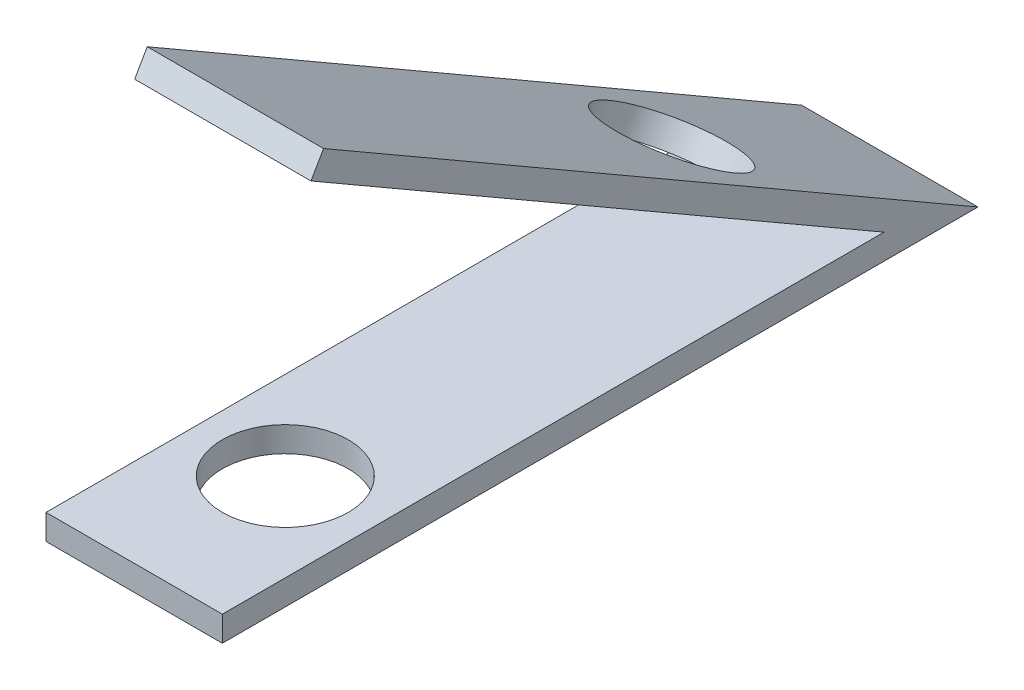
SolidWorks part; units mm, degrees
ref_plane "Front Plane" through (0, 0, 0) normal (0, 0, 1) x (1, 0, 0)
ref_plane "Top Plane" through (0, 0, 0) normal (0, 1, 0) x (1, 0, 0)
ref_plane "Right Plane" through (0, 0, 0) normal (1, 0, 0) x (0, 0, -1)
sketch "Sketch1" plane through (0, 0, 0) normal (1, 0, 0) x (0, 0, -1)
  line L0 (-227.4871, 131.3397) -> (0, 0)
  line L1 (0, 0) -> (-262.6795, 0)
  line L2 (-262.6795, 0) -> (-262.6795, -10)
  line L3 (-262.6795, -10) -> (37.3205, -10)
  line L4 (37.3205, -10) -> (-222.4871, 140)
  line L5 (-222.4871, 140) -> (-227.4871, 131.3397)
  dimension "D1" = 10
  dimension "D2" = 10
  dimension "D3" = 300
  dimension "D4" = 300
  dimension "D5" = 30
extrude "Boss-Extrude1" add sketch "Sketch1" along normal blind 70
sketch "Sketch2" plane through (0, 8.6603, -5) normal (0, 0.866, -0.5) x (1, 0, 0)
  line L0 (0, 37.3205) -> (0, -262.6795) construction
  line L3 (70, 37.3205) -> (0, 37.3205) construction
  circle A0 centre (35, -62.6795) radius 25
  dimension "D1" = 50
  dimension "D2" = 35
  dimension "D3" = 100
extrude "Cut-Extrude1" cut sketch "Sketch2" against normal blind 10
sketch "Sketch5" plane through (0, 0, 0) normal (0, 1, 0) x (1, 0, 0)
  line L0 (70, -262.6795) -> (0, -262.6795) construction
  line L1 (70, 37.3205) -> (70, -222.4871) construction
  circle A0 centre (35, -202.6795) radius 25
  dimension "D1" = 50
  dimension "D2" = 60
  dimension "D3" = 35
extrude "Cut-Extrude3" cut sketch "Sketch5" against normal blind 300
equation "\"mountAngle\" = 30deg"
equation "\"D5@Sketch1\"=\"mountAngle\""
equation "\"ThrusterDim\"= 140mm"
equation "\"hatchHoleDiameter\"= 600mm"
equation "\"hullThickness\"= 150mm"
equation "\"gasketHullInterconnectWidth\"= 100mm"
equation "\"collarThickness\"= 15"
equation "\"hatchTunnelLength\"=200"
equation "\"oRingDiameter\"=2"
equation "\"boltPatternRadiusInterconnect\"=500"
equation "\"interconnectBoltDiameter\"=30"
equation "\"hatchShaftDiameter\"=20"
equation "\"hatchMinima\"=50"
equation "\"hullDiameter\"=2000"
equation "\"hatchMaxima\"=180"
equation "\"bushingFlatHatch\"=15"
equation "\"hingePivotDiameter\"=20"
equation "\"handleWidth\"=250"
equation "\"handleHeight\"=160"
equation "\"handleThickness\"=25"
equation "\"FrameLength\"= 4300"
equation "\"FrameMidLength\"= 3000"
equation "\"TubeOD\"= 100"
equation "\"FrameBackFlat\"= 800"
equation "\"TubeWall\"=15"
equation "\"TopMemberAngle\"=120"
equation "\"FrameHight\"= 2500"
